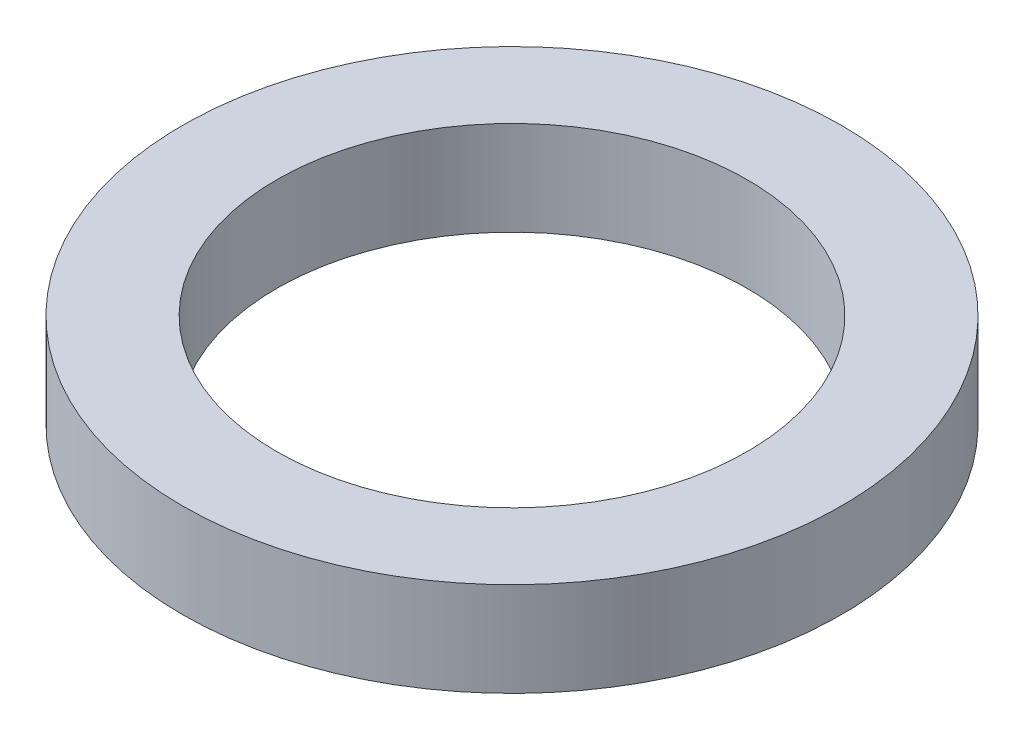
SolidWorks part; units mm, degrees
ref_plane "Front Plane" through (0, 0, 0) normal (0, 0, 1) x (1, 0, 0)
ref_plane "Top Plane" through (0, 0, 0) normal (0, 1, 0) x (1, 0, 0)
ref_plane "Right Plane" through (0, 0, 0) normal (1, 0, 0) x (0, 0, -1)
sketch "Sketch1" plane through (0, 0, 0) normal (0, 1, 0) x (1, 0, 0)
  circle A0 centre (0, 0) radius 2.5
  circle A1 centre (0, 0) radius 3.5
  dimension "D1" = 5
  dimension "D2" = 7
extrude "Boss-Extrude1" add sketch "Sketch1" along normal blind 1
equation "\"7mmx1mmSpacerDiameter\" = 7mm"
equation "\"D2@Sketch1\"=\"7mmx1mmSpacerDiameter\""
equation "\"7mmx1mmSpacerHeight\"= 1mm"
equation "\"D1@Boss-Extrude1\"=\"7mmx1mmSpacerHeight\""
